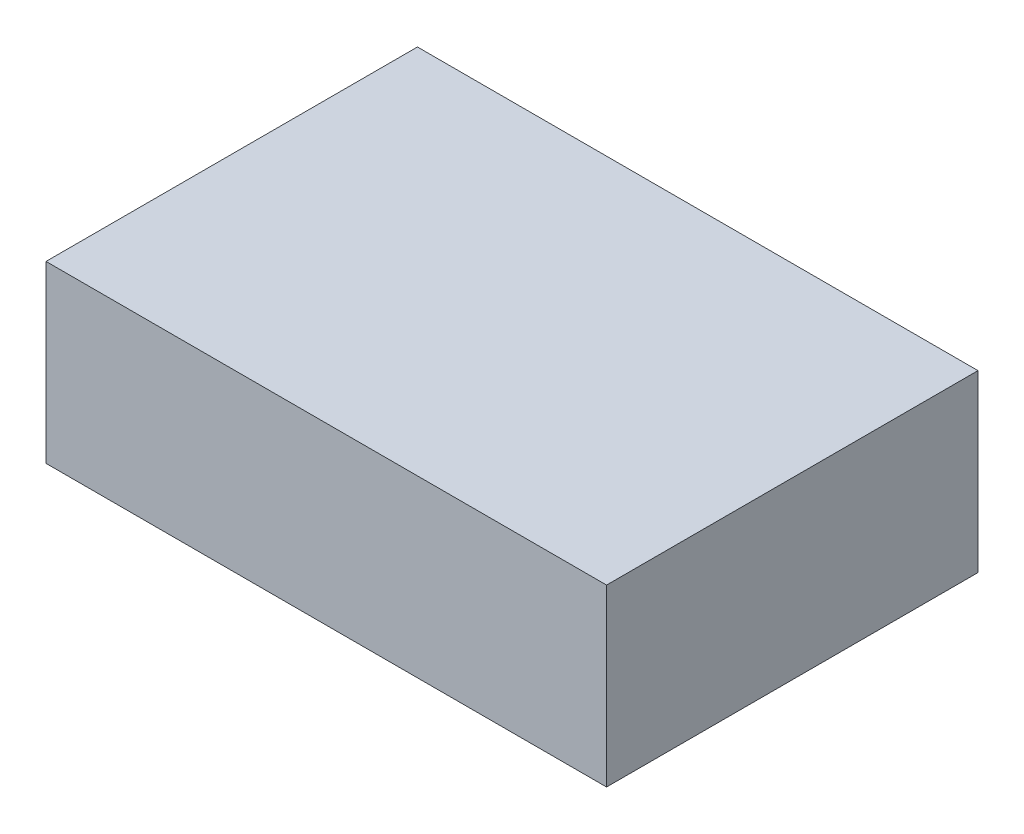
SolidWorks part; units mm, degrees
ref_plane "Front Plane" through (0, 0, 0) normal (0, 0, 1) x (1, 0, 0)
ref_plane "Top Plane" through (0, 0, 0) normal (0, 1, 0) x (1, 0, 0)
ref_plane "Right Plane" through (0, 0, 0) normal (1, 0, 0) x (0, 0, -1)
sketch "Sketch1" plane through (0, 38.1, 0) normal (0, 1, 0) x (1, 0, 0)
  line L1 (-160.2422, -1156.1779) -> (160.2422, -1156.1779)
  line L2 (-160.2422, -1156.1779) -> (-160.2422, -943.8221)
  line L3 (-160.2422, -943.8221) -> (160.2422, -943.8221)
  line L4 (160.2422, -1156.1779) -> (160.2422, -943.8221)
  line L5 (-160.2422, -1156.1779) -> (160.2422, -943.8221) construction
  line L6 (-160.2422, -943.8221) -> (160.2422, -1156.1779) construction
  point P0 (0, -1050)
  point P5 (160.2422, -1156.1779)
extrude "Boss-Extrude1" add sketch "Sketch1" along normal blind 100
